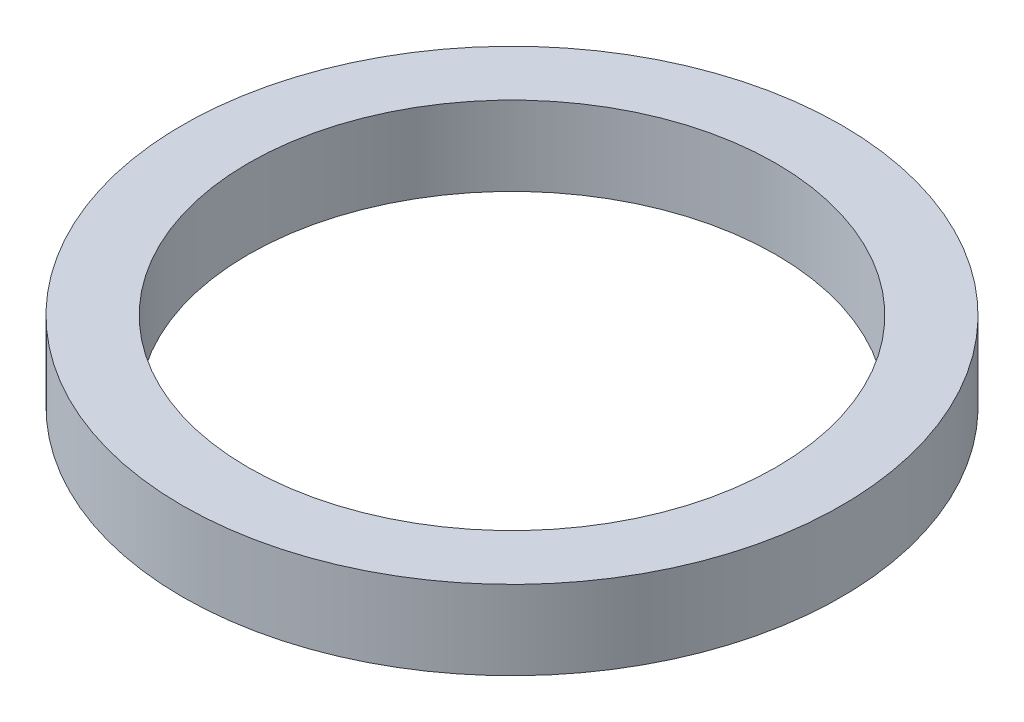
SolidWorks part; units mm, degrees
material "POLYURETHANE (11671)"
ref_plane "Front Plane" through (0, 0, 0) normal (0, 0, 1) x (1, 0, 0)
ref_plane "Top Plane" through (0, 0, 0) normal (0, 1, 0) x (1, 0, 0)
ref_plane "Right Plane" through (0, 0, 0) normal (1, 0, 0) x (0, 0, -1)
sketch "Sketch1" plane through (0, 0, 0) normal (0, 1, 0) x (1, 0, 0)
  circle A0 centre (0, 0) radius 25
  circle A1 centre (0, 0) radius 20
  dimension "D1" = 50
  dimension "D2" = 5
extrude "Boss-Extrude1" add sketch "Sketch1" along normal blind 6
